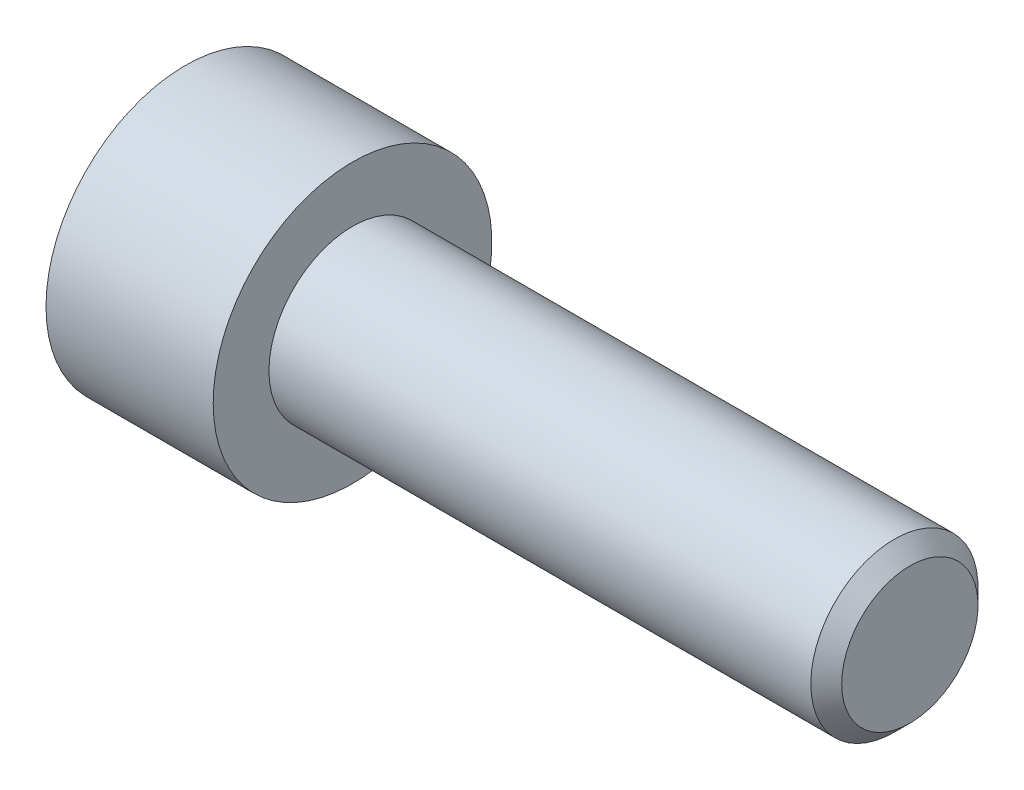
SolidWorks part; units mm, degrees
material "Alloy Steel"
ref_plane "Front Plane" through (0, 0, 0) normal (0, 0, 1) x (1, 0, 0)
ref_plane "Top Plane" through (0, 0, 0) normal (0, 1, 0) x (1, 0, 0)
ref_plane "Right Plane" through (0, 0, 0) normal (1, 0, 0) x (0, 0, -1)
sketch "BodySketch" plane through (0, 0, 0) normal (0, 1, 0) x (1, 0, 0)
  line L0 (-6, 0) -> (-6, 5)
  line L1 (-6, 5) -> (0, 5)
  line L2 (0, 5) -> (0, 3)
  line L3 (0, 3) -> (19.4455, 3)
  line L4 (20, 2.4455) -> (20, 0)
  line L5 (-6, 0) -> (20, 0) construction
  line L6 (19.4455, 3) -> (20, 2.4455)
  line L7 (-6, 0) -> (20, 0)
  dimension "Diameter" = 6
  dimension "Head_dia" = 10
  dimension "Head_ht" = 6
  dimension "Length" = 20
  dimension "Minor_dia" = 4.891
  dimension "Body_ch_ang" = 45
revolve "Base-Revolve" add sketch "BodySketch" angle 360 about L5
cosmetic thread "Thread" parameters "Thread_length"=17, "D2"=6.344
sketch "DriveSketch" plane through (-6, 0, 0) normal (-1, 0, 0) x (0, 0, 1)
  line L1 (2.8983, 0) -> (1.4491, 2.51)
  line L2 (1.4491, 2.51) -> (-1.4491, 2.51)
  line L3 (-1.4491, 2.51) -> (-2.8983, 0)
  line L4 (-2.8983, 0) -> (-1.4491, -2.51)
  line L5 (-1.4491, -2.51) -> (1.4491, -2.51)
  line L6 (1.4491, -2.51) -> (2.8983, 0)
  circle A0 centre (0, 0) radius 2.51 construction
  circle A1 centre (0, 0) radius 5 construction
  dimension "Hex_size" = 5.02
extrude "HexDrive" cut sketch "DriveSketch" against normal blind 3
other "Freeze***"
other "PropertyManager"
